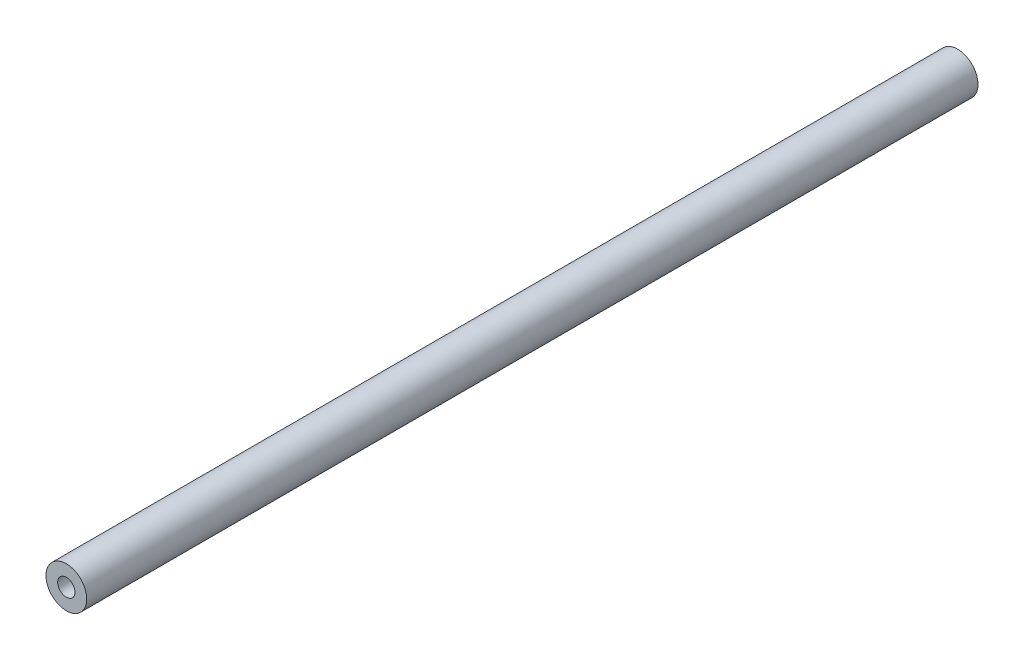
SolidWorks part; units mm, degrees
ref_plane "前视基准面" through (0, 0, 0) normal (0, 0, 1) x (1, 0, 0)
ref_plane "上视基准面" through (0, 0, 0) normal (0, 1, 0) x (1, 0, 0)
ref_plane "右视基准面" through (0, 0, 0) normal (1, 0, 0) x (0, 0, -1)
sketch "草图1" plane through (0, 0, 0) normal (0, 0, 1) x (1, 0, 0)
  circle A0 centre (0, 0) radius 8
  dimension "D1" = 16
extrude "凸台-拉伸1" add sketch "草图1" along normal blind 350
hole_wizard "M8 螺纹孔1" positions "3D草图2" profile "草图5" tap size "M8" standard "Gb"
sketch3d "3D草图2"
  line L0 (0, 0, 350) -> (0, 0, 0) construction
  point P0 (0, 0, 350)
  point P4 (0, 0, 0)
  point P8 (0, 0, 0)
  point P10 (0, 0, 0)
sketch "草图5" plane through (0, 0, 350) normal (1, 0, 0) x (0, -1, 0)
  line L0 (0, 0) -> (0, 28.2929)
  line L1 (0, 28.2929) -> (3.4, 26.25)
  line L2 (3.4, 26.25) -> (3.4, 0)
  line L5 (3.4, 0) -> (0, 0)
  line L10 (0, 28.2929) -> (-3.4, 26.25) construction
  line L11 (0, -6.35) -> (0, 107.95) construction
  dimension "螺纹孔钻头直径" = 6.8
  dimension "螺纹孔钻头深度" = 26.25
  dimension "导头角度" = 118
cosmetic thread "孔螺蚊线1"
cosmetic thread "孔螺蚊线2"
cosmetic thread "孔螺蚊线3"
cosmetic thread "孔螺蚊线4"
hole_wizard "M8 螺纹孔2" positions "草图7" profile "草图6" tap size "M8" standard "Gb"
sketch "草图7" plane through (0, 0, 0) normal (0, 0, -1) x (-1, 0, 0)
  point P0 (0, 0)
sketch "草图6" plane through (0, 0, 0) normal (1, 0, 0) x (0, 1, 0)
  line L0 (0, 0) -> (0, 28.2929)
  line L1 (0, 28.2929) -> (3.4, 26.25)
  line L2 (3.4, 26.25) -> (3.4, 0)
  line L5 (3.4, 0) -> (0, 0)
  line L10 (0, 28.2929) -> (-3.4, 26.25) construction
  line L11 (0, -6.35) -> (0, 107.95) construction
  dimension "螺纹孔钻头直径" = 6.8
  dimension "螺纹孔钻头深度" = 26.25
  dimension "导头角度" = 118
cosmetic thread "孔螺蚊线5"
